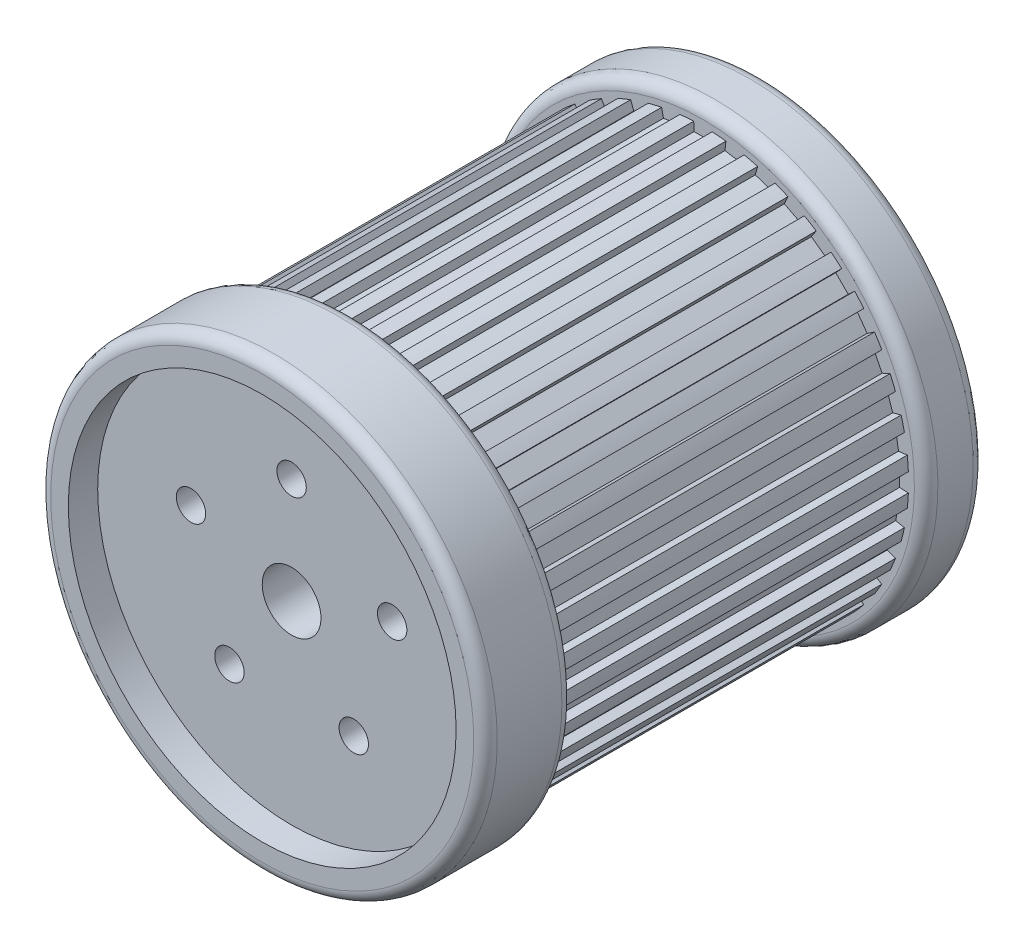
SolidWorks part; units mm, degrees
material "Teak"
ref_plane "Plano frontal" through (0, 0, 0) normal (0, 0, 1) x (1, 0, 0)
ref_plane "Plano superior" through (0, 0, 0) normal (0, 1, 0) x (1, 0, 0)
ref_plane "Plano direito" through (0, 0, 0) normal (1, 0, 0) x (0, 0, -1)
sketch "Sketch1" plane through (0, 0, 0) normal (1, 0, 0) x (0, 0, -1)
  line L0 (-27.1032, 0) -> (-37.1032, 0)
  line L1 (-37.1032, 0) -> (-37.1032, -35)
  line L2 (-37.1032, -35) -> (42.8968, -35)
  line L3 (42.8968, -35) -> (42.8968, -25)
  line L4 (42.8968, -25) -> (-27.1032, -25)
  line L5 (-27.1032, -25) -> (-27.1032, 0)
  dimension "D1" = 25
  dimension "D2" = 10
  dimension "D3" = 10
  dimension "D4" = 80
revolve "Revolve1" add sketch "Sketch1" angle 360 about L0
sketch "Sketch2" plane through (0, 0, 27.1032) normal (0, 0, -1) x (-1, 0, 0)
  circle A0 centre (0, 0) radius 18 construction
  circle A1 centre (0, 0) radius 5
  circle A2 centre (0, 18) radius 2.5
  circle A3 centre (17.119, 5.5623) radius 2.5
  circle A4 centre (10.5801, -14.5623) radius 2.5
  circle A5 centre (-10.5801, -14.5623) radius 2.5
  circle A6 centre (-17.119, 5.5623) radius 2.5
  point P17 (0, 0)
  dimension "D1" = 36
  dimension "D2" = 5
  dimension "D3" = 10
  dimension "D4" = 5
extrude "Cut-Extrude1" cut sketch "Sketch2" against normal through all
sketch "Sketch3" plane through (0, 0, -42.8968) normal (0, 0, -1) x (-1, 0, 0)
  line L0 (0, 0) -> (0, 33.4664) construction
  line L1 (-1.5, 33.4664) -> (1.5, 33.4664)
  line L2 (1.5, 33.4664) -> (1.5672, 34.9649)
  line L3 (-1.5, 33.4664) -> (-1.5672, 34.9649)
  circle A0 centre (0, 0) radius 35 construction
  arc A1 (1.5672, 34.9649) -> (-1.5672, 34.9649) centre (0, 0) ccw
  point P6 (0, 33.4664)
  dimension "D1" = 3
  dimension "D2" = 1.5
extrude "Cut-Extrude2" cut sketch "Sketch3" against normal blind 70
sketch "Sketch4" plane through (0, 0, 37.1032) normal (0, 0, 1) x (1, 0, 0)
  circle A0 centre (0, 0) radius 35 construction
  circle A1 centre (0, 0) radius 35
  circle A2 centre (0, 0) radius 38
  dimension "D1" = 3
extrude "Boss-Extrude1" add sketch "Sketch4" against normal up to surface (10 mm away) up to face at (0, 34.2244, 27.1032)
pattern_circular "CirPattern1" count 40 over 360 about axis through (0, 0, 0) along (0, 0, 1) of "Cut-Extrude2"
sketch "Sketch5" plane through (0, 0, 37.1032) normal (0, 0, 1) x (1, 0, 0)
  circle A0 centre (0, 0) radius 38 construction
  circle A1 centre (0, 0) radius 38
  circle A3 centre (0, 0) radius 33
  dimension "D1" = 5
extrude "Boss-Extrude2" add sketch "Sketch5" along normal blind 5
sketch "Sketch6" plane through (0, 0, -42.8968) normal (0, 0, -1) x (-1, 0, 0)
  circle A0 centre (0, 0) radius 32
  circle A1 centre (0, 0) radius 38 construction
  circle A2 centre (0, 0) radius 38
  dimension "D1" = 64
extrude "Boss-Extrude3" add sketch "Sketch6" against normal blind 10
fillet "Fillet1" radius 3 1 edges at (0, 25, -42.8968)
fillet "Fillet2" radius 2 4 edges at (0, 38, 27.1032) (38, 0, 42.1032) (0, 38, -32.8968) (0, 38, -42.8968)
